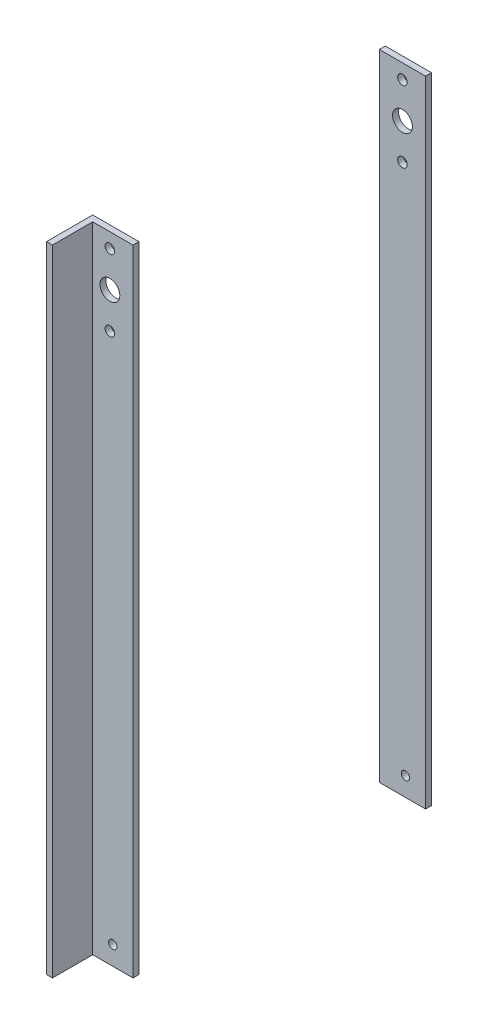
SolidWorks part; units mm, degrees
ref_plane "Front Plane" through (0, 0, 0) normal (0, 0, 1) x (1, 0, 0)
ref_plane "Top Plane" through (0, 0, 0) normal (0, 1, 0) x (1, 0, 0)
ref_plane "Right Plane" through (0, 0, 0) normal (1, 0, 0) x (0, 0, -1)
sketch "Sketch1" plane through (0, 0, 0) normal (1, 0, 0) x (0, 0, -1)
  line L1 (-11.65, 160) -> (11.65, 160)
  line L2 (-11.65, 160) -> (-11.65, -160)
  line L3 (-11.65, -160) -> (11.65, -160)
  line L4 (11.65, 160) -> (11.65, -160)
  line L5 (-11.65, 160) -> (11.65, -160) construction
  line L6 (-11.65, -160) -> (11.65, 160) construction
  point P0 (0, 0)
  dimension "D1" = 23.3
  dimension "D2" = 320
extrude "Boss-Extrude1" add sketch "Sketch1" along normal blind 3
sketch "Sketch2" plane through (3, 0, 0) normal (1, 0, 0) x (0, 0, -1)
  line L0 (-11.65, -160) -> (11.65, -160) construction
  line L1 (-11.65, 160) -> (-8.65, 160)
  line L2 (-11.65, 160) -> (-11.65, -160)
  line L3 (-11.65, -160) -> (-8.65, -160)
  line L4 (-8.65, 160) -> (-8.65, -160)
  dimension "D1" = 3
extrude "Boss-Extrude2" add sketch "Sketch2" along normal blind 20.3
sketch "Sketch3" plane through (0, 0, 11.65) normal (0, 0, 1) x (1, 0, 0)
  line L0 (11.65, 134.6) -> (11.65, 160) construction
  line L1 (23.3, 160) -> (0, 160) construction
  line L2 (11.65, 134.6) -> (11.65, 152.6) construction
  line L3 (11.65, 134.6) -> (11.65, 116.6) construction
  circle A0 centre (11.65, 134.6) radius 5
  circle A1 centre (11.65, 152.6) radius 2.4
  circle A2 centre (11.65, 116.6) radius 2.4
  dimension "D2" = 10
  dimension "D4" = 4.8
  dimension "D6" = 4.8
  dimension "D1" = 25.4
  dimension "D3" = 18
  dimension "D5" = 18
extrude "Cut-Extrude1" cut sketch "Sketch3" against normal blind 20.3 and the other way blind 34.3
ref_plane "Plane1" through (0, 0, 84.65) normal (0, 0, 1) x (1, 0, 0)
ref_plane "Plane2" through (0, 0, 156.15) normal (0, 0, 1) x (1, 0, 0)
sketch "Sketch5" plane through (0, 0, 156.15) normal (0, 0, 1) x (1, 0, 0)
  line L0 (11.65, 160) -> (11.65, -160) construction
  line L1 (23.3, 160) -> (0, 160) construction
  line L2 (23.3, -160) -> (0, -160) construction
  line L3 (11.65, 0) -> (23.4759, 0) construction
  line L4 (0, 160) -> (0, -160) construction
  line L5 (0, -160) -> (23.3, -160)
  line L6 (0, -160) -> (0, 160)
  line L7 (0, 160) -> (23.3, 160)
  line L8 (23.3, -160) -> (23.3, 160)
  line L9 (0, -160) -> (23.3, 160) construction
  line L10 (0, 160) -> (23.3, -160) construction
extrude "Boss-Extrude3" add sketch "Sketch5" along normal blind 3 separate body
sketch "Sketch6" plane through (0, 0, 159.15) normal (0, 0, 1) x (1, 0, 0)
  line L0 (0, -160) -> (23.3, -160) construction
  line L1 (0, 160) -> (3, 160)
  line L2 (0, 160) -> (0, -160)
  line L3 (0, -160) -> (3, -160)
  line L4 (3, 160) -> (3, -160)
  dimension "D1" = 3
extrude "Boss-Extrude4" add sketch "Sketch6" along normal blind 20.3
sketch "Sketch7" plane through (0, 0, 156.15) normal (0, 0, -1) x (-1, 0, 0)
  line L0 (-11.65, 134.6) -> (-11.65, 160) construction
  line L1 (-23.3, 160) -> (0, 160) construction
  line L2 (-9.2822, 134.6) -> (-13.7042, 134.6) construction
  line L3 (-13.7042, 134.6) -> (-11.65, 134.6) construction
  line L4 (-11.65, 134.6) -> (-11.65, 116.6) construction
  circle A0 centre (-11.65, 134.6) radius 5
  circle A1 centre (-11.65, 116.6) radius 2.4
  circle A2 centre (-11.65, 152.6) radius 2.4
  dimension "D1" = 10
  dimension "D3" = 4.8
  dimension "D2" = 18
extrude "Cut-Extrude2" cut sketch "Sketch7" against normal blind 20.3
sketch "Sketch9" plane through (0, 0, 159.15) normal (0, 0, 1) x (1, 0, 0)
  line L0 (13.15, -160) -> (13.15, -150.45) construction
  line L1 (3, -160) -> (23.3, -160) construction
  circle A0 centre (13.15, -150.45) radius 2.1
  dimension "D2" = 4.2
  dimension "D1" = 9.55
extrude "Cut-Extrude3" cut sketch "Sketch9" against normal blind 151
sketch "Sketch10" plane through (3, 0, 0) normal (1, 0, 0) x (0, 0, -1)
  line L0 (11.65, -160) -> (11.65, 160) construction
  line L1 (-8.65, 160) -> (11.65, 160)
  line L2 (-8.65, 160) -> (-8.65, 108)
  line L3 (-8.65, 108) -> (11.65, 108)
  line L4 (11.65, 160) -> (11.65, 108)
  dimension "D1" = 52
extrude "Cut-Extrude4" cut sketch "Sketch10" against normal blind 151
